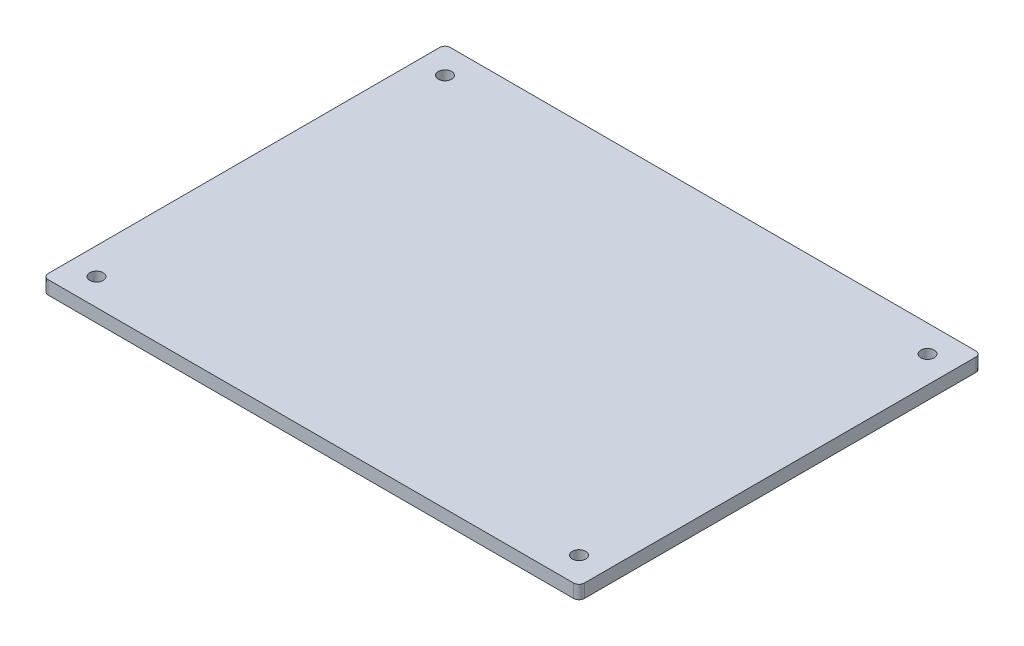
SolidWorks part; units mm, degrees
material "Perspex (TM) GS Acrylic Cast Sheet"
ref_plane "Front Plane" through (0, 0, 0) normal (0, 0, 1) x (1, 0, 0)
ref_plane "Top Plane" through (0, 0, 0) normal (0, 1, 0) x (1, 0, 0)
ref_plane "Right Plane" through (0, 0, 0) normal (1, 0, 0) x (0, 0, -1)
sketch "Sketch1" plane through (0, 0, 0) normal (0, 1, 0) x (1, 0, 0)
  line L1 (0, 0) -> (200, 0)
  line L2 (0, 0) -> (0, 150)
  line L3 (0, 150) -> (200, 150)
  line L4 (200, 0) -> (200, 150)
  dimension "D1" = 200
  dimension "D2" = 150
extrude "Boss-Extrude1" add sketch "Sketch1" along normal blind 5
fillet "Fillet1" radius 2 4 edges at (0, 2.5, 0) (0, 2.5, -150) (200, 2.5, -150) (200, 2.5, 0)
sketch "Sketch2" plane through (0, 5, 0) normal (0, 1, 0) x (1, 0, 0)
  line L0 (198, 150) -> (2, 150) construction
  line L1 (0, 148) -> (0, 2) construction
  line L2 (200, 2) -> (200, 148) construction
  line L4 (2, 0) -> (198, 0) construction
  circle A0 centre (10, 140) radius 2.5
  circle A1 centre (190, 140) radius 2.5
  circle A2 centre (190, 10) radius 2.5
  circle A3 centre (10, 10) radius 2.5
  dimension "D1" = 5
  dimension "D2" = 10
  dimension "D3" = 10
  dimension "D4" = 10
  dimension "D5" = 10
  dimension "D6" = 10
  dimension "D7" = 10
  dimension "D8" = 10
  dimension "D9" = 10
extrude "Cut-Extrude1" cut sketch "Sketch2" against normal up to next
